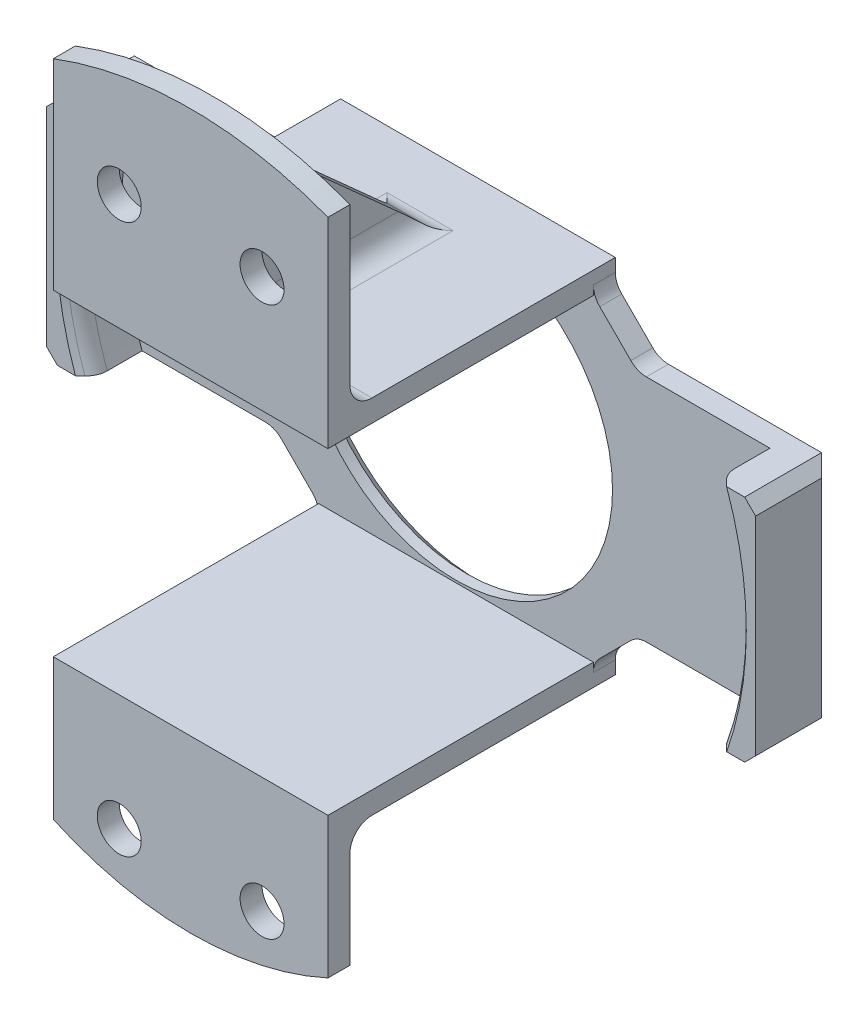
SolidWorks part; units mm, degrees
material "ABS"
ref_plane "Front Plane" through (0, 0, 0) normal (0, 0, 1) x (1, 0, 0)
ref_plane "Top Plane" through (0, 0, 0) normal (0, 1, 0) x (1, 0, 0)
ref_plane "Right Plane" through (0, 0, 0) normal (1, 0, 0) x (0, 0, -1)
sketch "Sketch1" plane through (0, 0, 0) normal (1, 0, 0) x (0, 0, -1)
  line L0 (0, 35) -> (0, 14.45)
  line L1 (0, 14.45) -> (24.15, 14.45)
  line L2 (24.15, 14.45) -> (24.15, -14.45)
  line L3 (24.15, -14.45) -> (0, -14.45)
  line L4 (0, -14.45) -> (0, -35)
  line L5 (2, 35) -> (2, 16.45)
  line L6 (2, 16.45) -> (26.15, 16.45)
  line L7 (26.15, 16.45) -> (26.15, -16.45)
  line L8 (26.15, -16.45) -> (2, -16.45)
  line L9 (2, -16.45) -> (2, -35)
  line L10 (2, 35) -> (0, 35)
  line L11 (2, -35) -> (0, -35)
  point P3 (24.15, 0)
  dimension "D1" = 24.15
  dimension "D2" = 28.9
  dimension "D3" = 70
  dimension "D4" = 2
extrude "Boss-Extrude1" add sketch "Sketch1" along normal mid plane 25
sketch "Sketch2" plane through (0, 0, 0) normal (0, 0, 1) x (1, 0, 0)
  circle A0 centre (0, 0) radius 35
  dimension "D1" = 70
extrude "Cut-Extrude-Thin1" cut sketch "Sketch2" against normal blind 10 thin
sketch "Sketch3" plane through (0, 0, 0) normal (0, 0, 1) x (1, 0, 0)
  line L0 (12.5, -32.6917) -> (12.5, -27.2718)
  line L1 (12.5, -14.45) -> (12.5, -32.6917) construction
  line L3 (-12.5, -32.6917) -> (-12.5, -27.2718)
  line L4 (-12.5, -14.45) -> (-12.5, -32.6917) construction
  arc A0 (-12.5, -27.2718) -> (12.5, -27.2718) centre (0, 0) ccw
  arc A1 (-12.5, -32.6917) -> (12.5, -32.6917) centre (0, 0) ccw
  dimension "D1" = 60
  dimension "D2" = 70
extrude "Cut-Extrude1" cut sketch "Sketch3" against normal blind 10
sketch "Sketch4" plane through (0, 0, 0) normal (1, 0, 0) x (0, 0, -1)
  line L0 (14.075, 16.45) -> (14.075, 14.45)
  line L1 (26.15, 16.45) -> (2, 16.45) construction
  line L2 (0, 14.45) -> (24.15, 14.45) construction
  line L3 (14.075, 14.45) -> (24.15, 14.45)
  line L4 (24.15, 14.45) -> (24.15, -14.45)
  line L5 (24.15, -14.45) -> (14.075, -14.45)
  line L6 (24.15, -14.45) -> (0, -14.45) construction
  line L7 (14.075, -14.45) -> (14.075, -16.45)
  line L8 (2, -16.45) -> (26.15, -16.45) construction
  line L9 (14.075, -16.45) -> (26.15, -16.45)
  line L10 (26.15, -16.45) -> (26.15, 16.45)
  line L11 (26.15, 16.45) -> (14.075, 16.45)
extrude "Boss-Extrude2" add sketch "Sketch4" along normal mid plane 64.55
sketch "Sketch5" plane through (0, 0, -26.15) normal (0, 0, -1) x (-1, 0, 0)
  circle A0 centre (0, 0) radius 14.25
  dimension "D1" = 28.5
extrude "Cut-Extrude2" cut sketch "Sketch5" against normal blind 40
chamfer "Chamfer1" distance 5 angle 45 4 edges at (12.5, -15.45, -14.075) (-12.5, -15.45, -14.075) (-12.5, 15.45, -14.075) (12.5, 15.45, -14.075)
chamfer "Chamfer2" distance 1 angle 45 1 edges at (-14.25, 0, -26.15)
sketch "Sketch6" plane through (0, 0, -24.15) normal (0, 0, 1) x (1, 0, 0)
  line L0 (-32.275, -14.45) -> (-32.275, 14.45)
  line L1 (-32.275, 14.45) -> (-26.7746, 14.45)
  line L2 (32.275, 14.45) -> (-32.275, 14.45) construction
  line L3 (-32.275, -14.45) -> (-26.7746, -14.45)
  line L4 (0, 0) -> (0, 35) construction
  line L5 (32.275, -14.45) -> (26.7746, -14.45)
  line L6 (32.275, 14.45) -> (26.7746, 14.45)
  line L7 (32.275, -14.45) -> (32.275, 14.45)
  arc A0 (-26.7746, 14.45) -> (-26.7746, -14.45) centre (0, 0) ccw
  arc A1 (26.7746, 14.45) -> (26.7746, -14.45) centre (0, 0) cw
  arc A2 (12.5, 32.6917) -> (-12.5, 32.6917) centre (0, 0) ccw construction
  dimension "D1" = 60.85
extrude "Boss-Extrude3" add sketch "Sketch6" along normal blind 5
chamfer "Chamfer3" distance 5 angle 45 4 edges at (-32.275, 16.45, -20.1125) (-32.275, -16.45, -20.1125) (32.275, -16.45, -20.1125) (32.275, 16.45, -20.1125)
fillet "Fillet1" radius 3 4 edges at (-28.0248, -14.45, -19.15) (28.0248, -14.45, -19.15) (28.0248, 14.45, -19.15) (-28.0248, 14.45, -19.15)
sketch "Sketch7" plane through (0, 0, 0) normal (1, 0, 0) x (0, 0, -1)
  line L0 (2, 32.6917) -> (20.1125, 16.45)
  line L2 (14.075, 16.45) -> (26.15, 16.45) construction
rib "Rib2" sketch "Sketch7" sketch "Sketch7" thickness 2 extrusion direction parallel to sketch draft on no parameters "D1"=2
sketch "Sketch8" plane through (0, 0, 0) normal (1, 0, 0) x (0, 0, -1)
  line L0 (20.1125, -16.45) -> (2, -27.2718)
  line L1 (26.15, -16.45) -> (14.075, -16.45) construction
rib "Rib3" sketch "Sketch8" sketch "Sketch8" thickness 2 extrusion direction parallel to sketch draft on no parameters "D1"=2
sketch "Sketch9" plane through (0, 0, -26.15) normal (0, 0, -1) x (-1, 0, 0)
  line L0 (12.5, 14.45) -> (12.5, 16.45)
  line L1 (-27.275, 16.45) -> (27.275, 16.45) construction
  line L2 (-27.275, 16.45) -> (-32.275, 11.45)
  line L3 (32.275, 11.45) -> (32.275, 10.45)
  line L4 (32.275, -11.45) -> (32.275, 11.45) construction
  line L5 (32.275, 10.45) -> (16.5, 10.45)
  line L6 (16.5, 10.45) -> (12.5, 14.45)
  line L7 (0, 16.45) -> (0, -16.45) construction
  line L8 (-1, -16.45) -> (1, -16.45) construction
  line L9 (-12.5, 16.45) -> (-27.275, 16.45)
  line L10 (-16.5, 10.45) -> (-12.5, 14.45)
  line L11 (-32.275, 10.45) -> (-16.5, 10.45)
  line L12 (-32.275, 11.45) -> (-32.275, 10.45)
  line L13 (-12.5, 14.45) -> (-12.5, 16.45)
  line L14 (-32.275, 0) -> (32.275, 0) construction
  line L15 (-32.275, -11.45) -> (-32.275, 11.45) construction
  line L16 (27.275, -16.45) -> (32.275, -11.45)
  line L17 (12.5, -16.45) -> (27.275, -16.45)
  line L18 (-12.5, -14.45) -> (-12.5, -16.45)
  line L19 (-32.275, -11.45) -> (-32.275, -10.45)
  line L20 (-32.275, -10.45) -> (-16.5, -10.45)
  line L21 (-16.5, -10.45) -> (-12.5, -14.45)
  line L22 (-12.5, -16.45) -> (-27.275, -16.45)
  line L23 (16.5, -10.45) -> (12.5, -14.45)
  line L24 (32.275, -10.45) -> (16.5, -10.45)
  line L25 (32.275, -11.45) -> (32.275, -10.45)
  line L27 (12.5, 16.45) -> (27.275, 16.45)
  line L28 (27.275, 16.45) -> (32.275, 11.45)
  line L29 (-27.275, -16.45) -> (-32.275, -11.45)
  line L30 (12.5, -14.45) -> (12.5, -16.45)
  dimension "D2" = 1
extrude "Cut-Extrude3" cut sketch "Sketch9" against normal through all
chamfer "Chamfer4" distance 1 angle 45 2 edges at (-30.425, 0, -19.15) (30.425, 0, -19.15)
sketch "Sketch10" plane through (0, 0, -2) normal (0, 0, -1) x (-1, 0, 0)
  line L1 (-6.5, -25) -> (6.5, -25) construction
  line L2 (-6.5, -25) -> (-6.5, 25) construction
  line L3 (-6.5, 25) -> (6.5, 25) construction
  line L4 (6.5, -25) -> (6.5, 25) construction
  line L5 (-6.5, -25) -> (6.5, 25) construction
  line L6 (-6.5, 25) -> (6.5, -25) construction
  circle A0 centre (6.5, 25) radius 2
  circle A1 centre (-6.5, 25) radius 2
  circle A2 centre (-6.5, -25) radius 2
  circle A3 centre (6.5, -25) radius 2
  point P2 (0, 0)
  dimension "D1" = 4
  dimension "D2" = 13
  dimension "D3" = 50
extrude "Cut-Extrude4" cut sketch "Sketch10" against normal blind 5
chamfer "Chamfer5" distance 1 angle 45 6 edges at (32.275, -10.45, -22.65) (32.275, 10.45, -22.65) (32.275, 0, -26.15) (-32.275, -10.45, -22.65) (-32.275, 0, -26.15) (-32.275, 10.45, -22.65)
fillet "Fillet2" radius 2 26 edges at (-30.425, 0, -20.15) (30.425, 0, -20.15) (12.5, 14.45, -25.15) (-12.5, 14.45, -25.15) (-12.5, -14.45, -25.15) (12.5, -14.45, -25.15) (16.5, -10.45, -25.15) (16.5, 10.45, -25.15) (-16.5, 10.45, -25.15) (-16.5, -10.45, -25.15) (6.75, -16.45, -2) (-6.75, -16.45, -2) (-6.75, 16.45, -2) (6.75, 16.45, -2) (0, -27.2718, -2) (0, 32.6917, -2) (0, 16.45, -20.1125) (0, -16.45, -20.1125) (1, -21.8609, -2) (1, -16.45, -11.0563) (-1, -21.8609, -2) (-1, -16.45, -11.0563) (-1, 24.5709, -2) (-1, 16.45, -11.0563) (1, 24.5709, -2) (1, 16.45, -11.0563)
sketch "Sketch11" plane through (0, 0, -2) normal (0, 0, -1) x (-1, 0, 0)
  circle A0 centre (6.5, 25) radius 3.5 construction
  circle A1 centre (-6.5, 25) radius 3.5 construction
  circle A2 centre (6.5, -25) radius 3.5 construction
  circle A3 centre (-6.5, -25) radius 3.5 construction
  dimension "D1" = 7
